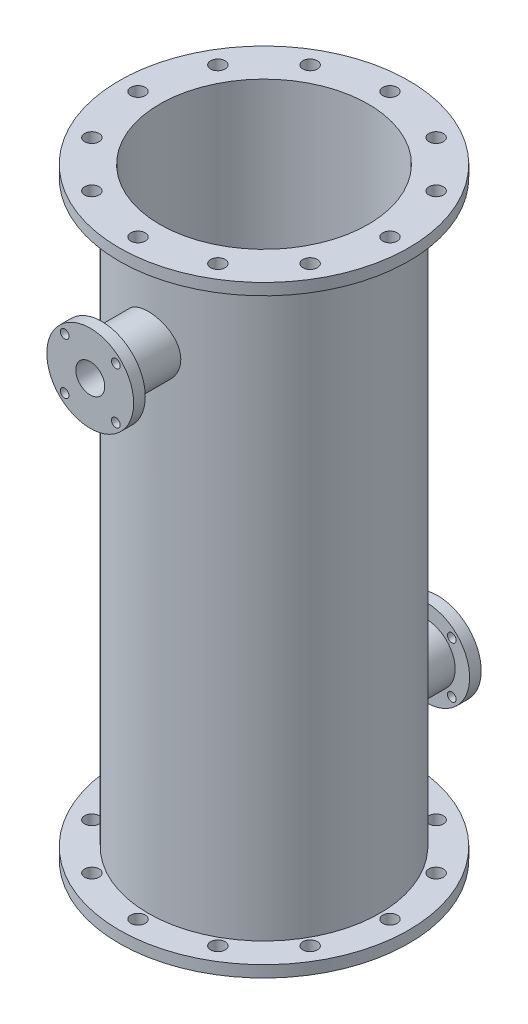
SolidWorks part; units mm, degrees
ref_plane "Front Plane" through (0, 0, 0) normal (0, 0, 1) x (1, 0, 0)
ref_plane "Top Plane" through (0, 0, 0) normal (0, 1, 0) x (1, 0, 0)
ref_plane "Right Plane" through (0, 0, 0) normal (1, 0, 0) x (0, 0, -1)
sketch "Sketch1" plane through (0, 0, 0) normal (0, 1, 0) x (1, 0, 0)
  circle A0 centre (0, 0) radius 250
  circle A1 centre (0, 217.5) radius 12.5
  circle A2 centre (108.75, 188.3605) radius 12.5
  circle A3 centre (188.3605, 108.75) radius 12.5
  circle A4 centre (217.5, 0) radius 12.5
  circle A5 centre (188.3605, -108.75) radius 12.5
  circle A6 centre (108.75, -188.3605) radius 12.5
  circle A7 centre (0, -217.5) radius 12.5
  circle A8 centre (-108.75, -188.3605) radius 12.5
  circle A9 centre (-188.3605, -108.75) radius 12.5
  circle A10 centre (-217.5, 0) radius 12.5
  circle A11 centre (-188.3605, 108.75) radius 12.5
  circle A12 centre (-108.75, 188.3605) radius 12.5
  point P29 (0, 0)
  dimension "D1" = 500
  dimension "D2" = 25
  dimension "D3" = 217.5
  dimension "D5" = 217.5
  dimension "D4" = 12
extrude "Boss-Extrude1" add sketch "Sketch1" along normal blind 20
sketch "Sketch2" plane through (0, 20, 0) normal (0, 1, 0) x (1, 0, 0)
  circle A0 centre (0, 0) radius 200
  dimension "D1" = 400
extrude "Boss-Extrude2" add sketch "Sketch2" along normal blind 1000
sketch "Sketch3" plane through (0, 1020, 0) normal (0, 1, 0) x (1, 0, 0)
  circle A0 centre (0, 0) radius 250
  circle A1 centre (0, 217.5) radius 12.5
  circle A2 centre (108.75, 188.3605) radius 12.5
  circle A3 centre (188.3605, 108.75) radius 12.5
  circle A4 centre (217.5, 0) radius 12.5
  circle A5 centre (188.3605, -108.75) radius 12.5
  circle A6 centre (108.75, -188.3605) radius 12.5
  circle A7 centre (0, -217.5) radius 12.5
  circle A8 centre (-108.75, -188.3605) radius 12.5
  circle A9 centre (-188.3605, -108.75) radius 12.5
  circle A10 centre (-217.5, 0) radius 12.5
  circle A11 centre (-188.3605, 108.75) radius 12.5
  circle A12 centre (-108.75, 188.3605) radius 12.5
  point P31 (0, 0)
  dimension "D1" = 500
  dimension "D3" = 25
  dimension "D2" = 217.5
  dimension "D5" = 217.5
  dimension "D4" = 12
extrude "Boss-Extrude3" add sketch "Sketch3" along normal blind 20
sketch "Sketch4" plane through (0, 1040, 0) normal (0, 1, 0) x (1, 0, 0)
  circle A0 centre (0, 0) radius 180
  dimension "D1" = 360
extrude "Cut-Extrude1" cut sketch "Sketch4" against normal blind 1040
ref_plane "Plane2" through (0, 0, -200) normal (0, 0, -1) x (-1, 0, 0)
sketch "Sketch6" plane through (0, 0, -200) normal (0, 0, -1) x (-1, 0, 0)
  line L0 (0, 170) -> (0, 20) construction
  line L1 (250, 20) -> (-250, 20) construction
  circle A0 centre (0, 170) radius 50
  dimension "D1" = 100
  dimension "D2" = 150
extrude "Boss-Extrude5" add sketch "Sketch6" along normal blind 80 and the other way blind 10
sketch "Sketch7" plane through (0, 0, -280) normal (0, 0, -1) x (-1, 0, 0)
  line L0 (0, 170) -> (0, 245) construction
  line L1 (0, 170) -> (44.1942, 214.1942) construction
  line L2 (0, 170) -> (-44.1942, 125.8058) construction
  circle A0 centre (0, 170) radius 75
  circle A1 centre (44.1942, 214.1942) radius 7.5
  circle A2 centre (44.1942, 125.8058) radius 7.5
  circle A3 centre (-44.1942, 125.8058) radius 7.5
  circle A4 centre (-44.1942, 214.1942) radius 7.5
  point P15 (0, 170)
  dimension "D1" = 150
  dimension "D2" = 15
  dimension "D3" = 62.5
  dimension "D4" = 45
  dimension "D6" = 180
  dimension "D7" = 125
  dimension "D5" = 4
extrude "Boss-Extrude6" add sketch "Sketch7" along normal blind 20
sketch "Sketch8" plane through (0, 0, -300) normal (0, 0, -1) x (-1, 0, 0)
  circle A0 centre (0, 170) radius 25
  dimension "D1" = 50
extrude "Cut-Extrude2" cut sketch "Sketch8" against normal blind 142
ref_plane "Plane3" through (0, 0, 200) normal (0, 0, 1) x (1, 0, 0)
sketch "Sketch9" plane through (0, 0, 200) normal (0, 0, 1) x (1, 0, 0)
  line L0 (0, 870) -> (0, 1020) construction
  circle A0 centre (0, 870) radius 50
  point P2 (0, 0)
  dimension "D1" = 100
  dimension "D2" = 150
extrude "Boss-Extrude7" add sketch "Sketch9" along normal blind 80 and the other way blind 13
sketch "Sketch10" plane through (0, 0, 280) normal (0, 0, 1) x (1, 0, 0)
  line L0 (0, 870) -> (0, 945) construction
  line L1 (0, 870) -> (44.1942, 914.1942) construction
  line L2 (0, 870) -> (-44.1942, 825.8058) construction
  circle A0 centre (0, 870) radius 75
  circle A1 centre (44.1942, 914.1942) radius 7.5
  circle A2 centre (44.1942, 825.8058) radius 7.5
  circle A3 centre (-44.1942, 825.8058) radius 7.5
  circle A4 centre (-44.1942, 914.1942) radius 7.5
  point P15 (0, 870)
  dimension "D1" = 150
  dimension "D2" = 15
  dimension "D3" = 62.5
  dimension "D4" = 45
  dimension "D6" = 180
  dimension "D7" = 62.5
  dimension "D5" = 4
extrude "Boss-Extrude8" add sketch "Sketch10" along normal blind 20
sketch "Sketch11" plane through (0, 0, 300) normal (0, 0, 1) x (1, 0, 0)
  circle A2 centre (0, 870) radius 25
  dimension "D1" = 50
extrude "Cut-Extrude3" cut sketch "Sketch11" against normal blind 145
